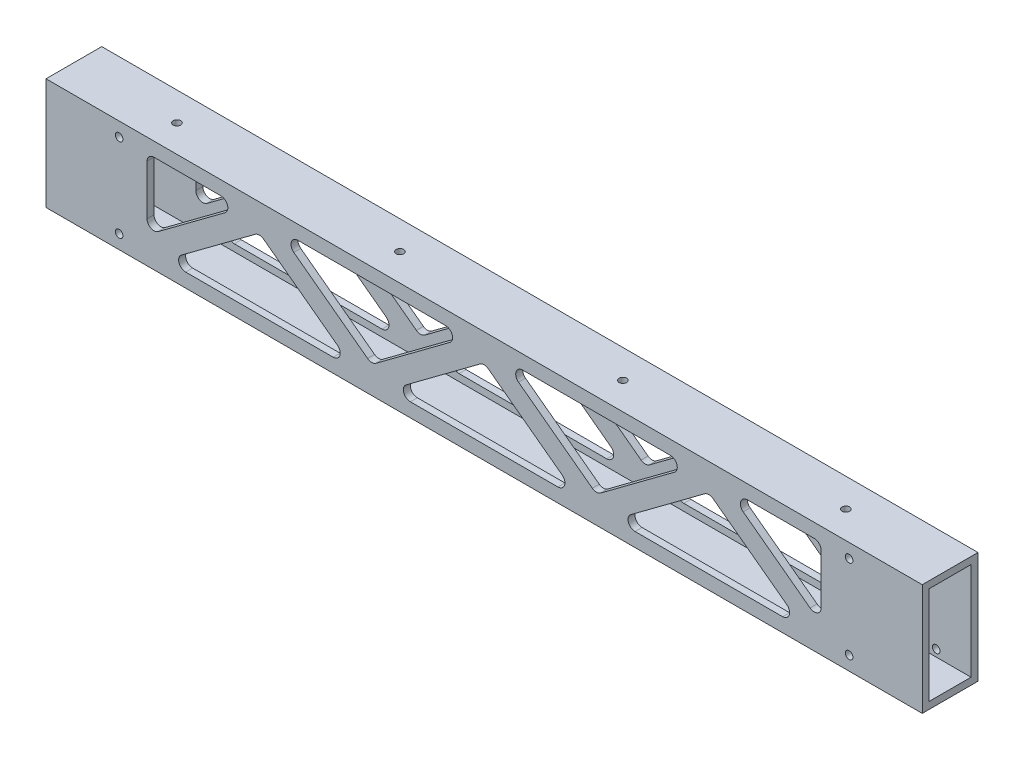
SolidWorks part; units mm, degrees
material "6061-T6 (SS)"
ref_plane "Front Plane" through (0, 0, 0) normal (0, 0, 1) x (1, 0, 0)
ref_plane "Top Plane" through (0, 0, 0) normal (0, 1, 0) x (1, 0, 0)
ref_plane "Right Plane" through (0, 0, 0) normal (1, 0, 0) x (0, 0, -1)
sketch "Sketch1" plane through (0, 0, 0) normal (1, 0, 0) x (0, 0, -1)
  line L0 (-9.525, 22.225) -> (-9.525, 25.4) construction
  line L1 (12.7, -25.4) -> (-12.7, -25.4)
  line L2 (12.7, -25.4) -> (12.7, 25.4)
  line L3 (12.7, 25.4) -> (-12.7, 25.4)
  line L4 (-12.7, -25.4) -> (-12.7, 25.4)
  line L5 (12.7, -25.4) -> (-12.7, 25.4) construction
  line L6 (12.7, 25.4) -> (-12.7, -25.4) construction
  line L7 (-9.525, -22.225) -> (9.525, -22.225)
  line L8 (-9.525, -22.225) -> (-9.525, 22.225)
  line L9 (-9.525, 22.225) -> (9.525, 22.225)
  line L10 (9.525, -22.225) -> (9.525, 22.225)
  line L11 (-9.525, -22.225) -> (9.525, 22.225) construction
  line L12 (-9.525, 22.225) -> (9.525, -22.225) construction
  line L13 (-9.525, 22.225) -> (-12.7, 22.225) construction
  point P0 (0, 0)
  point P6 (0, 0)
  dimension "D1" = 50.8
  dimension "D2" = 25.4
  dimension "D3" = 3.175
extrude "Boss-Extrude1" add sketch "Sketch1" along normal mid plane 399.2499
hole_wizard "#8-32 Tapped Hole1" positions "Sketch3" profile "Sketch2" tap size "#8-32" standard "ANSI Inch"
sketch "Sketch3" plane through (0, 0, 12.7) normal (0, 0, 1) x (1, 0, 0)
  line L0 (4.4926, 0) -> (-49995.5074, 0) construction
  line L1 (199.6249, 25.4) -> (199.6249, -25.4) construction
  line L2 (0, 0) -> (0, 50000) construction
  point P0 (166.2875, 19.05)
  point P2 (166.2875, -19.05)
  point P17 (-166.2875, 19.05)
  point P19 (-166.2875, -19.05)
  dimension "D1" = 38.1
  dimension "D2" = 33.3375
sketch "Sketch2" plane through (166.2875, 19.05, 12.7) normal (1, 0, 0) x (0, -1, 0)
  line L0 (0, 0) -> (0, 3.175)
  line L1 (0, 3.175) -> (1.7272, 3.175)
  line L2 (1.7272, 3.175) -> (1.7272, 0)
  line L5 (1.7272, 0) -> (0, 0)
  line L11 (0, -6.35) -> (0, 107.95) construction
  dimension "Thru Tap Drill Dia." = 3.4544
  dimension "Thru Tap Drill Depth" = 3.175
cosmetic thread "Hole Thread1" parameters "D2"=4.1656
cosmetic thread "Hole Thread2" parameters "D2"=4.1656
cosmetic thread "Hole Thread3" parameters "D2"=4.1656
cosmetic thread "Hole Thread4" parameters "D2"=4.1656
sketch "Sketch5" plane through (0, 0, 12.7) normal (0, 0, 1) x (1, 0, 0)
  line L0 (-153.5875, -3.068) -> (-153.5875, 49996.932) construction
  line L1 (153.5875, -1.1829) -> (153.5875, 49998.8171) construction
  line L2 (-83.0391, 19.05) -> (-50083.0391, 19.05) construction
  line L3 (-96.8631, -19.05) -> (-50096.8631, -19.05) construction
  line L4 (-153.5874, 25.4) -> (-153.5875, 19.05) construction
  line L5 (199.6249, 25.4) -> (-199.6249, 25.4) construction
  line L6 (-153.5875, -19.05) -> (-153.5874, -25.4) construction
  line L7 (199.6249, -25.4) -> (-199.6249, -25.4) construction
  line L8 (-153.5875, -19.05) -> (-102.3916, 19.05) construction
  line L9 (-102.3916, 19.05) -> (-51.1958, -19.05) construction
  line L10 (-51.1958, -19.05) -> (0, 19.05) construction
  line L11 (0, 19.05) -> (51.1958, -19.05) construction
  line L12 (51.1958, -19.05) -> (102.3916, 19.05) construction
  line L13 (102.3916, 19.05) -> (153.5875, -19.05) construction
  line L14 (-153.5875, 19.05) -> (-153.5875, -13.1134)
  line L15 (-153.5875, -13.1134) -> (-110.3688, 19.05)
  line L16 (-110.3688, 19.05) -> (-153.5875, 19.05)
  line L17 (-145.6103, -19.05) -> (-102.3916, 13.1134)
  line L18 (-102.3916, 13.1134) -> (-59.173, -19.05)
  line L19 (-59.173, -19.05) -> (-145.6103, -19.05)
  line L20 (-94.4145, 19.05) -> (-7.9771, 19.05)
  line L21 (-7.9771, 19.05) -> (-51.1958, -13.1134)
  line L22 (-51.1958, -13.1134) -> (-94.4145, 19.05)
  line L23 (-43.2187, -19.05) -> (0, 13.1134)
  line L24 (0, 13.1134) -> (43.2187, -19.05)
  line L25 (43.2187, -19.05) -> (-43.2187, -19.05)
  line L26 (94.4145, 19.05) -> (51.1958, -13.1134)
  line L27 (51.1958, -13.1134) -> (7.9771, 19.05)
  line L28 (7.9771, 19.05) -> (94.4145, 19.05)
  line L29 (59.173, -19.05) -> (102.3916, 13.1134)
  line L30 (102.3916, 13.1134) -> (145.6103, -19.05)
  line L31 (145.6103, -19.05) -> (59.173, -19.05)
  line L32 (110.3688, 19.05) -> (153.5875, 19.05)
  line L33 (153.5875, 19.05) -> (153.5875, -13.1134)
  line L34 (153.5875, -13.1134) -> (110.3688, 19.05)
  circle A0 centre (-166.2875, 19.05) radius 12.7 construction
  circle A1 centre (166.2875, 19.05) radius 12.7 construction
  dimension "D1" = 25.4
  dimension "D2" = 6.35
  dimension "D3" = 9.525
extrude "Cut-Extrude2" cut sketch "Sketch5" against normal through all
fillet "Fillet1" radius 3.175 42 edges at (110.3688, 19.05, 11.1125) (110.3688, 19.05, -11.1125) (153.5875, 19.05, 11.1125) (153.5875, 19.05, -11.1125) (153.5875, -13.1134, 11.1125) (153.5875, -13.1134, -11.1125) (145.6103, -19.05, 11.1125) (145.6103, -19.05, -11.1125) (102.3916, 13.1134, 11.1125) (102.3916, 13.1134, -11.1125) (59.173, -19.05, -11.1125) (59.173, -19.05, 11.1125) (7.9771, 19.05, -11.1125) (7.9771, 19.05, 11.1125) (51.1958, -13.1134, 11.1125) (51.1958, -13.1134, -11.1125) (94.4145, 19.05, 11.1125) (94.4145, 19.05, -11.1125) (0, 13.1134, 11.1125) (0, 13.1134, -11.1125) (43.2187, -19.05, 11.1125) (43.2187, -19.05, -11.1125) (-43.2187, -19.05, 11.1125) (-43.2187, -19.05, -11.1125) (-7.9771, 19.05, 11.1125) (-7.9771, 19.05, -11.1125) (-51.1958, -13.1134, 11.1125) (-51.1958, -13.1134, -11.1125) (-59.173, -19.05, 11.1125) (-59.173, -19.05, -11.1125) (-102.3916, 13.1134, 11.1125) (-102.3916, 13.1134, -11.1125) (-94.4145, 19.05, 11.1125) (-94.4145, 19.05, -11.1125) (-153.5875, 19.05, 11.1125) (-153.5875, 19.05, -11.1125) (-110.3688, 19.05, 11.1125) (-110.3688, 19.05, -11.1125) (-145.6103, -19.05, -11.1125) (-145.6103, -19.05, 11.1125) (-153.5875, -13.1134, -11.1125) (-153.5875, -13.1134, 11.1125)
hole_wizard "#8-32 Tapped Hole2" positions "Sketch7" profile "Sketch8" tap size "#8-32" standard "ANSI Inch"
sketch "Sketch7" plane through (0, 0, -12.7) normal (0, 0, -1) x (-1, 0, 0)
  line L0 (0, 0) -> (0, 50000) construction
  line L1 (-199.6249, 0) -> (-50199.6249, 0) construction
  line L2 (-199.6249, -25.4) -> (-199.6249, 25.4) construction
  point P0 (-183.7499, 19.05)
  point P2 (-183.7499, -19.05)
  point P4 (183.7499, -19.05)
  point P6 (183.7499, 19.05)
  point P16 (-199.6249, 0)
  dimension "D1" = 38.1
  dimension "D2" = 15.875
sketch "Sketch8" plane through (183.7499, 19.05, -12.7) normal (1, 0, 0) x (0, 1, 0)
  line L0 (0, 0) -> (0, 3.175)
  line L1 (0, 3.175) -> (1.7272, 3.175)
  line L2 (1.7272, 3.175) -> (1.7272, 0)
  line L5 (1.7272, 0) -> (0, 0)
  line L11 (0, -6.35) -> (0, 107.95) construction
  dimension "Thru Tap Drill Dia." = 3.4544
  dimension "Thru Tap Drill Depth" = 3.175
cosmetic thread "Hole Thread5" parameters "D2"=4.1656
cosmetic thread "Hole Thread6" parameters "D2"=4.1656
cosmetic thread "Hole Thread7" parameters "D2"=4.1656
cosmetic thread "Hole Thread8" parameters "D2"=4.1656
hole_wizard "#8-32 Tapped Hole3" positions "Sketch10" profile "Sketch9" tap size "#8-32" standard "ANSI Inch"
sketch "Sketch10" plane through (0, 25.4, 0) normal (0, 1, 0) x (1, 0, 0)
  line L0 (0, 0) -> (0, 50000) construction
  line L1 (-158.4143, -0.2718) -> (-50158.4143, -0.2718) construction
  line L2 (199.6249, -12.7) -> (-199.6249, -12.7) construction
  point P0 (-152.4, -0.2718)
  point P2 (-50.8, -0.2718)
  point P4 (50.8, -0.2718)
  point P6 (152.4, -0.2718)
  dimension "D1" = 12.4282
  dimension "D2" = 101.6
  dimension "D3" = 101.6
sketch "Sketch9" plane through (-152.4, 25.4, 0.2718) normal (1, 0, 0) x (0, 0, 1)
  line L0 (0, 0) -> (0, 3.175)
  line L1 (0, 3.175) -> (1.7272, 3.175)
  line L2 (1.7272, 3.175) -> (1.7272, 0)
  line L5 (1.7272, 0) -> (0, 0)
  line L11 (0, -6.35) -> (0, 107.95) construction
  dimension "Thru Tap Drill Dia." = 3.4544
  dimension "Thru Tap Drill Depth" = 3.175
cosmetic thread "Hole Thread9" parameters "D2"=4.1656
cosmetic thread "Hole Thread10" parameters "D2"=4.1656
cosmetic thread "Hole Thread11" parameters "D2"=4.1656
cosmetic thread "Hole Thread12" parameters "D2"=4.1656
equation "\"D2@Sketch3\"=1+.25+1/16"
